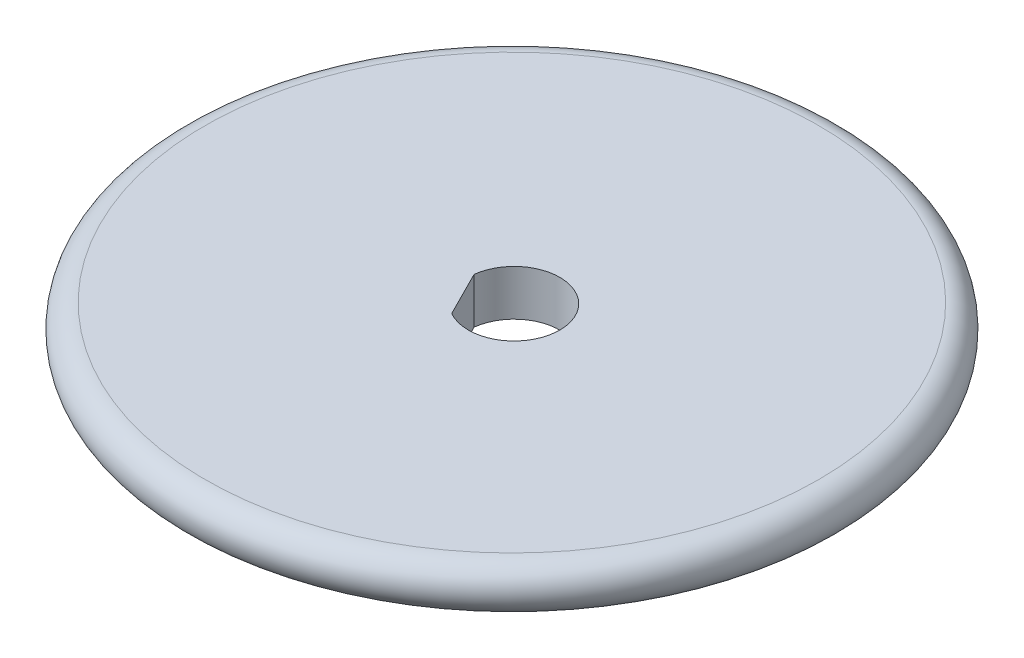
SolidWorks part; units mm, degrees
ref_plane "Front Plane" through (0, 0, 0) normal (0, 0, 1) x (1, 0, 0)
ref_plane "Top Plane" through (0, 0, 0) normal (0, 1, 0) x (1, 0, 0)
ref_plane "Right Plane" through (0, 0, 0) normal (1, 0, 0) x (0, 0, -1)
sketch "Sketch2" plane through (0, 0, 0) normal (0, 0, 1) x (1, 0, 0)
  line L0 (0, 15.7234) -> (0, 18.2634)
  line L1 (0, 18.2634) -> (17.0415, 18.2634)
  line L2 (5.08, 15.7234) -> (17.0415, 15.7234)
  line L6 (5.08, 15.7234) -> (0, 15.7234)
  arc A0 (17.0415, 18.2634) -> (17.0415, 15.7234) centre (17.0415, 16.9934) cw
  dimension "D1" = 2.54
revolve "Revolve1" add sketch "Sketch2" angle 360 about L0
sketch "Sketch3" plane through (0, 18.2634, 0) normal (0, 1, 0) x (1, 0, 0)
  line L0 (-1.1451, -2.2008) -> (-2.4077, 0.3035)
  arc A0 (-1.1451, -2.2008) -> (-2.4077, 0.3035) centre (0.1147, 0.0047) ccw
extrude "Cut-Extrude1" cut sketch "Sketch3" against normal through all
